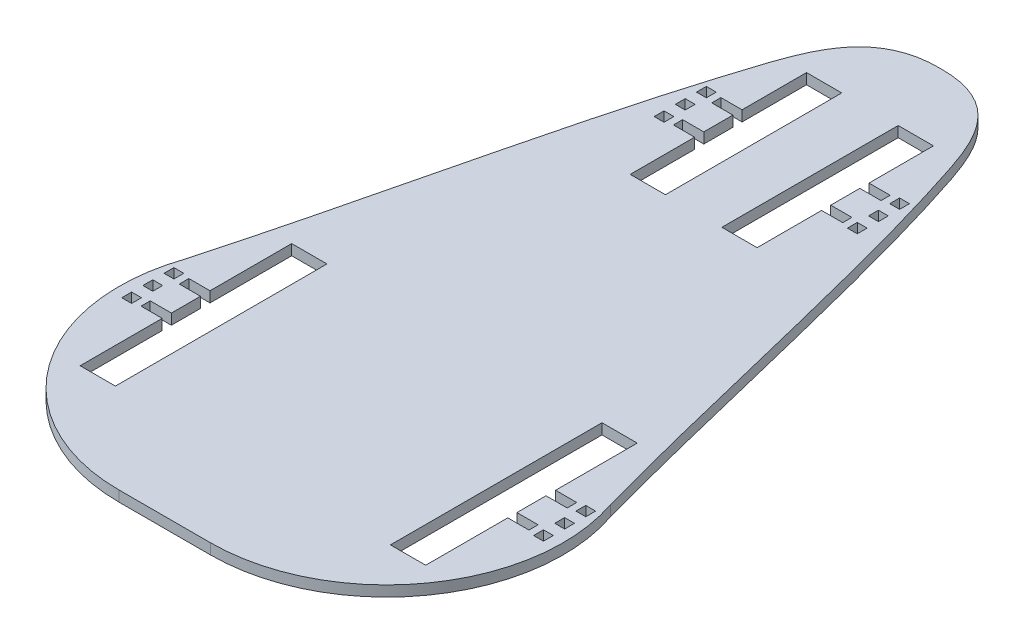
SolidWorks part; units mm, degrees
ref_plane "Front Plane" through (0, 0, 0) normal (0, 0, 1) x (1, 0, 0)
ref_plane "Top Plane" through (0, 0, 0) normal (0, 1, 0) x (1, 0, 0)
ref_plane "Right Plane" through (0, 0, 0) normal (1, 0, 0) x (0, 0, -1)
sketch "Sketch1" plane through (0, 0, 0) normal (0, 1, 0) x (1, 0, 0)
  line L0 (54.9211, 210.7172) -> (54.9211, -9.2828) construction
  line L1 (41.947, -9.2828) -> (67.8952, -9.2828)
  line L6 (5.9211, 75.7172) -> (15.9211, 75.7172)
  line L7 (54.9211, -9.2828) -> (64.9211, -9.2828)
  line L8 (54.9211, -9.2828) -> (44.9211, -9.2828)
  line L9 (5.9211, 75.7172) -> (5.9211, 15.7172)
  line L10 (5.9211, 15.7172) -> (15.9211, 15.7172)
  line L11 (15.9211, 75.7172) -> (15.9211, 15.7172)
  line L12 (5.9211, 75.7172) -> (15.9211, 15.7172) construction
  line L13 (5.9211, 15.7172) -> (15.9211, 75.7172) construction
  line L18 (-0.0789, 52.5482) -> (5.9211, 52.5482)
  line L19 (-0.0789, 52.5482) -> (-0.0789, 49.8422)
  line L35 (103.9211, 15.7172) -> (93.9211, 15.7172)
  line L36 (93.9211, 75.7172) -> (93.9211, 15.7172)
  line L37 (103.9211, 75.7172) -> (93.9211, 75.7172)
  line L38 (103.9211, 75.7172) -> (103.9211, 15.7172)
  line L40 (36.9211, 190.7172) -> (46.9211, 190.7172)
  line L41 (36.9211, 190.7172) -> (36.9211, 140.7172)
  line L42 (36.9211, 140.7172) -> (46.9211, 140.7172)
  line L43 (46.9211, 190.7172) -> (46.9211, 140.7172)
  line L44 (36.9211, 190.7172) -> (46.9211, 140.7172) construction
  line L45 (36.9211, 140.7172) -> (46.9211, 190.7172) construction
  line L46 (10.9211, 45.7172) -> (-10.3167, 45.7172) construction
  line L63 (72.9211, 140.7172) -> (62.9211, 140.7172)
  line L64 (62.9211, 190.7172) -> (62.9211, 140.7172)
  line L65 (72.9211, 190.7172) -> (62.9211, 190.7172)
  line L66 (72.9211, 190.7172) -> (72.9211, 140.7172)
  line L78 (114.7211, 47.1172) -> (111.9211, 44.3172) construction
  line L79 (114.7211, 44.3172) -> (111.9211, 47.1172) construction
  line L80 (114.7211, 50.3172) -> (111.9211, 53.1172) construction
  line L81 (114.7211, 53.1172) -> (111.9211, 50.3172) construction
  line L82 (109.9211, 38.9922) -> (103.9211, 41.5922) construction
  line L83 (109.9211, 41.5922) -> (103.9211, 38.9922) construction
  line L84 (109.9211, 49.8422) -> (103.9211, 52.5482) construction
  line L85 (109.9211, 52.5482) -> (103.9211, 49.8422) construction
  line L86 (111.9211, 41.1172) -> (111.9211, 38.3172)
  line L87 (114.7211, 38.3172) -> (111.9211, 38.3172)
  line L88 (114.7211, 41.1172) -> (114.7211, 38.3172)
  line L89 (111.9211, 44.3172) -> (111.9211, 47.1172)
  line L90 (114.7211, 47.1172) -> (111.9211, 47.1172)
  line L91 (114.7211, 44.3172) -> (114.7211, 47.1172)
  line L92 (41.9211, 165.7172) -> (25.0295, 165.7172) construction
  line L93 (30.9211, 172.4422) -> (36.9211, 172.4422)
  line L94 (30.9211, 172.4422) -> (30.9211, 169.8422)
  line L95 (30.9211, 169.8422) -> (36.9211, 169.8422)
  line L96 (36.9211, 172.4422) -> (36.9211, 169.8422)
  line L97 (30.9211, 172.4422) -> (36.9211, 169.8422) construction
  line L98 (30.9211, 169.8422) -> (36.9211, 172.4422) construction
  line L103 (26.1211, 161.1172) -> (28.9211, 161.1172)
  line L104 (26.1211, 173.1172) -> (28.9211, 173.1172)
  line L105 (30.9211, 161.5922) -> (36.9211, 161.5922)
  line L106 (30.9211, 161.5922) -> (30.9211, 158.9922)
  line L107 (30.9211, 158.9922) -> (36.9211, 158.9922)
  line L108 (36.9211, 161.5922) -> (36.9211, 158.9922)
  line L109 (30.9211, 161.5922) -> (36.9211, 158.9922) construction
  line L110 (30.9211, 158.9922) -> (36.9211, 161.5922) construction
  line L111 (26.1211, 173.1172) -> (26.1211, 170.3172)
  line L112 (26.1211, 170.3172) -> (28.9211, 170.3172)
  line L113 (28.9211, 173.1172) -> (28.9211, 170.3172)
  line L114 (26.1211, 173.1172) -> (28.9211, 170.3172) construction
  line L115 (26.1211, 170.3172) -> (28.9211, 173.1172) construction
  line L116 (26.1211, 164.3172) -> (28.9211, 164.3172)
  line L117 (26.1211, 164.3172) -> (26.1211, 167.1172)
  line L118 (26.1211, 167.1172) -> (28.9211, 167.1172)
  line L119 (28.9211, 164.3172) -> (28.9211, 167.1172)
  line L120 (26.1211, 164.3172) -> (28.9211, 167.1172) construction
  line L121 (26.1211, 167.1172) -> (28.9211, 164.3172) construction
  line L122 (26.1211, 161.1172) -> (26.1211, 158.3172)
  line L123 (26.1211, 158.3172) -> (28.9211, 158.3172)
  line L124 (28.9211, 161.1172) -> (28.9211, 158.3172)
  line L125 (83.7211, 167.1172) -> (80.9211, 164.3172) construction
  line L126 (83.7211, 164.3172) -> (80.9211, 167.1172) construction
  line L127 (83.7211, 170.3172) -> (80.9211, 173.1172) construction
  line L128 (83.7211, 173.1172) -> (80.9211, 170.3172) construction
  line L129 (78.9211, 158.9922) -> (72.9211, 161.5922) construction
  line L130 (78.9211, 161.5922) -> (72.9211, 158.9922) construction
  line L131 (78.9211, 169.8422) -> (72.9211, 172.4422) construction
  line L132 (78.9211, 172.4422) -> (72.9211, 169.8422) construction
  line L133 (80.9211, 161.1172) -> (80.9211, 158.3172)
  line L134 (83.7211, 158.3172) -> (80.9211, 158.3172)
  line L135 (83.7211, 161.1172) -> (83.7211, 158.3172)
  line L136 (80.9211, 164.3172) -> (80.9211, 167.1172)
  line L137 (83.7211, 167.1172) -> (80.9211, 167.1172)
  line L138 (83.7211, 164.3172) -> (83.7211, 167.1172)
  line L139 (83.7211, 164.3172) -> (80.9211, 164.3172)
  line L140 (80.9211, 173.1172) -> (80.9211, 170.3172)
  line L141 (83.7211, 170.3172) -> (80.9211, 170.3172)
  line L142 (83.7211, 173.1172) -> (83.7211, 170.3172)
  line L143 (72.9211, 161.5922) -> (72.9211, 158.9922)
  line L144 (78.9211, 158.9922) -> (72.9211, 158.9922)
  line L145 (78.9211, 161.5922) -> (78.9211, 158.9922)
  line L146 (78.9211, 161.5922) -> (72.9211, 161.5922)
  line L147 (83.7211, 173.1172) -> (80.9211, 173.1172)
  line L148 (83.7211, 161.1172) -> (80.9211, 161.1172)
  line L149 (72.9211, 172.4422) -> (72.9211, 169.8422)
  line L150 (78.9211, 169.8422) -> (72.9211, 169.8422)
  line L151 (78.9211, 172.4422) -> (78.9211, 169.8422)
  line L152 (78.9211, 172.4422) -> (72.9211, 172.4422)
  line L153 (-0.0789, 49.8422) -> (5.9211, 49.8422)
  line L154 (5.9211, 52.5482) -> (5.9211, 49.8422)
  line L155 (-0.0789, 52.5482) -> (5.9211, 49.8422) construction
  line L156 (-0.0789, 49.8422) -> (5.9211, 52.5482) construction
  line L157 (-4.8789, 41.1172) -> (-2.0789, 41.1172)
  line L158 (-4.8789, 53.1172) -> (-2.0789, 53.1172)
  line L159 (-0.0789, 41.5922) -> (5.9211, 41.5922)
  line L160 (-0.0789, 41.5922) -> (-0.0789, 38.9922)
  line L161 (-0.0789, 38.9922) -> (5.9211, 38.9922)
  line L162 (5.9211, 41.5922) -> (5.9211, 38.9922)
  line L163 (-0.0789, 41.5922) -> (5.9211, 38.9922) construction
  line L164 (-0.0789, 38.9922) -> (5.9211, 41.5922) construction
  line L165 (-4.8789, 53.1172) -> (-4.8789, 50.3172)
  line L166 (-4.8789, 50.3172) -> (-2.0789, 50.3172)
  line L167 (-2.0789, 53.1172) -> (-2.0789, 50.3172)
  line L168 (-4.8789, 53.1172) -> (-2.0789, 50.3172) construction
  line L169 (-4.8789, 50.3172) -> (-2.0789, 53.1172) construction
  line L170 (-4.8789, 44.3172) -> (-2.0789, 44.3172)
  line L171 (-4.8789, 44.3172) -> (-4.8789, 47.1172)
  line L172 (-4.8789, 47.1172) -> (-2.0789, 47.1172)
  line L173 (-2.0789, 44.3172) -> (-2.0789, 47.1172)
  line L174 (-4.8789, 44.3172) -> (-2.0789, 47.1172) construction
  line L175 (-4.8789, 47.1172) -> (-2.0789, 44.3172) construction
  line L176 (-4.8789, 41.1172) -> (-4.8789, 38.3172)
  line L177 (-4.8789, 38.3172) -> (-2.0789, 38.3172)
  line L178 (-2.0789, 41.1172) -> (-2.0789, 38.3172)
  line L179 (114.7211, 44.3172) -> (111.9211, 44.3172)
  line L180 (111.9211, 53.1172) -> (111.9211, 50.3172)
  line L181 (114.7211, 50.3172) -> (111.9211, 50.3172)
  line L182 (114.7211, 53.1172) -> (114.7211, 50.3172)
  line L183 (103.9211, 41.5922) -> (103.9211, 38.9922)
  line L184 (109.9211, 38.9922) -> (103.9211, 38.9922)
  line L185 (109.9211, 41.5922) -> (109.9211, 38.9922)
  line L186 (109.9211, 41.5922) -> (103.9211, 41.5922)
  line L187 (114.7211, 53.1172) -> (111.9211, 53.1172)
  line L188 (114.7211, 41.1172) -> (111.9211, 41.1172)
  line L189 (103.9211, 52.5482) -> (103.9211, 49.8422)
  line L190 (109.9211, 49.8422) -> (103.9211, 49.8422)
  line L191 (109.9211, 52.5482) -> (109.9211, 49.8422)
  line L192 (109.9211, 52.5482) -> (103.9211, 52.5482)
  line L193 (103.9211, 45.7172) -> (5.9211, 45.7172) construction
  arc A0 (41.947, -9.2828) -> (-5.4028, 56.7793) centre (41.947, 40.7172) cw
  arc A1 (67.8952, -9.2828) -> (115.245, 56.7793) centre (67.8952, 40.7172) ccw
  spline S0 degree 3 poles (54.9211, 210.7172) (54.0308, 210.7172) (36.7248, 210.3077) (26.6736, 181.7821) (12.5146, 130.3071) (2.5819, 85.5886) (-5.4028, 56.7793) knots 0 0 0 0 0.011068 0.221366 0.459883 1 1 1 1
  spline S1 degree 3 poles (54.9211, 210.7172) (55.8114, 210.7172) (73.1174, 210.3077) (83.1686, 181.7821) (97.3276, 130.3071) (107.2603, 85.5886) (115.245, 56.7793) knots 0 0 0 0 0.011068 0.221366 0.459883 1 1 1 1
  point P4 (2.9211, 51.1952)
  point P21 (120, 0)
  point P24 (10.9211, 45.7172)
  point P30 (-3.4789, 51.7172)
  point P33 (2.9211, 40.2922)
  point P40 (-3.4789, 45.7172)
  point P50 (41.9211, 165.7172)
  point P67 (33.9211, 171.1422)
  point P82 (27.5211, 171.7172)
  point P85 (33.9211, 160.2922)
  point P92 (27.5211, 165.7172)
  point P121 (82.3211, 165.7172)
  point P122 (75.9211, 160.2922)
  point P123 (82.3211, 171.7172)
  point P124 (75.9211, 171.1422)
  point P131 (113.3211, 45.7172)
  point P132 (106.9211, 40.2922)
  point P133 (113.3211, 51.7172)
  point P134 (106.9211, 51.1952)
  dimension "D6" = 10
  dimension "D7" = 50
  dimension "D10" = 6
  dimension "D2" = 173.1277
  dimension "D1" = 220
  dimension "D3" = 60.3239
  dimension "D4" = 10
  dimension "D5" = 10
  dimension "D8" = 60
  dimension "D9" = 6
  dimension "D11" = 25
  dimension "D12" = 2.8
  dimension "D13" = 2.8
  dimension "D14" = 2.8
  dimension "D15" = 2.8
  dimension "D16" = 2
  dimension "D17" = 2
  dimension "D18" = 39
  dimension "D19" = 2.8
  dimension "D20" = 10
  dimension "D21" = 50
  dimension "D22" = 20
  dimension "D23" = 8
  dimension "D24" = 8.25
  dimension "D25" = 0
  dimension "D26" = 0
  dimension "D27" = 3.2
  dimension "D28" = 3.2
  dimension "D29" = 8.25
  dimension "D30" = 4.125
  dimension "D33" = 2.8
  dimension "D34" = 6
  dimension "D35" = 2.6
  dimension "D36" = 8.25
  dimension "D37" = 4.125
  dimension "D38" = 2.6
  dimension "D39" = 6
  dimension "D40" = 0
  dimension "D41" = 0
  dimension "D42" = 2.8
  dimension "D43" = 2.8
  dimension "D44" = 2.8
  dimension "D45" = 2.8
  dimension "D46" = 2
  dimension "D47" = 2
  dimension "D48" = 3.2
  dimension "D49" = 2.8
  dimension "D50" = 2.8
  dimension "D51" = 3.2
  dimension "D52" = 2
  dimension "D53" = 52
  dimension "D54" = 2
extrude "Boss-Extrude1" add sketch "Sketch1" along normal blind 3 contours L0 S0 A0 L1 | S1 L0 L1 A1
